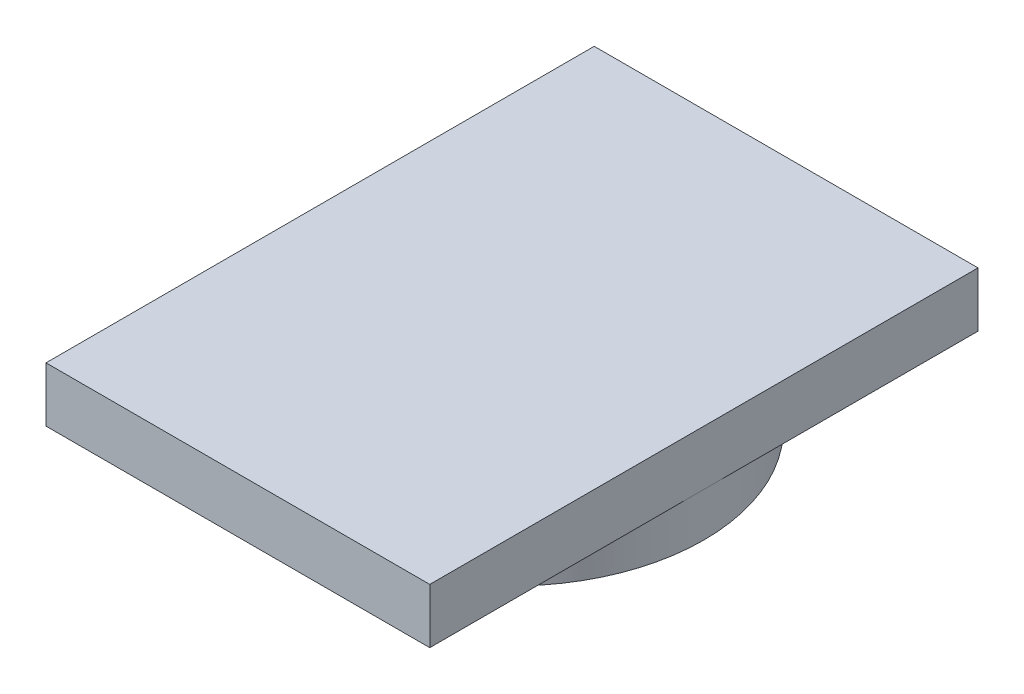
SolidWorks part; units mm, degrees
material "Acrylic (Medium-high impact)"
ref_plane "Front Plane" through (0, 0, 0) normal (0, 0, 1) x (1, 0, 0)
ref_plane "Top Plane" through (0, 0, 0) normal (0, 1, 0) x (1, 0, 0)
ref_plane "Right Plane" through (0, 0, 0) normal (1, 0, 0) x (0, 0, -1)
sketch "Sketch1" plane through (0, 0, 0) normal (0, 1, 0) x (1, 0, 0)
  circle A0 centre (0, 0) radius 3.5
  dimension "D1" = 7
extrude "Boss-Extrude1" add sketch "Sketch1" along normal blind 0.8
sketch "Sketch2" plane through (0, 0.8, 0) normal (0, 1, 0) x (1, 0, 0)
  line L1 (3.5, -5) -> (-3.5, -5)
  line L2 (3.5, -5) -> (3.5, 5)
  line L3 (3.5, 5) -> (-3.5, 5)
  line L4 (-3.5, -5) -> (-3.5, 5)
  line L5 (3.5, -5) -> (-3.5, 5) construction
  line L6 (3.5, 5) -> (-3.5, -5) construction
  point P0 (0, 0)
  dimension "D1" = 10
  dimension "D2" = 7
extrude "Boss-Extrude2" add sketch "Sketch2" along normal blind 1
